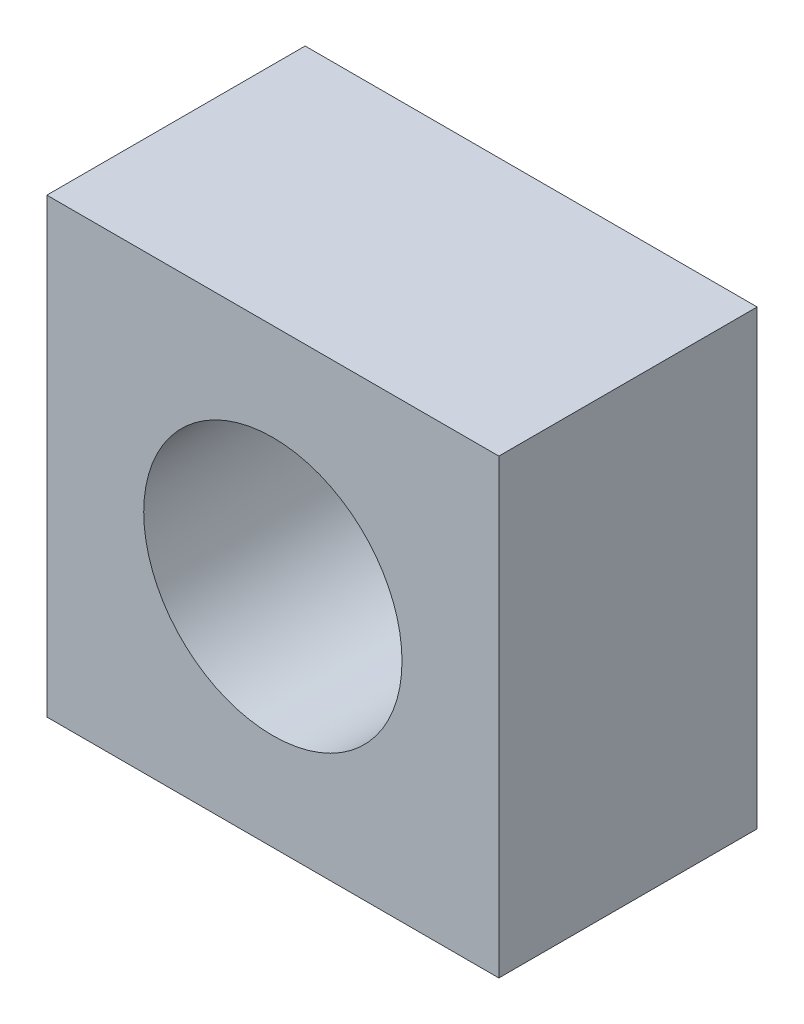
SolidWorks part; units mm, degrees
material "Tin Bearing Bronze"
ref_plane "Front Plane" through (0, 0, 0) normal (0, 0, 1) x (1, 0, 0)
ref_plane "Top Plane" through (0, 0, 0) normal (0, 1, 0) x (1, 0, 0)
ref_plane "Right Plane" through (0, 0, 0) normal (1, 0, 0) x (0, 0, -1)
sketch "Sketch1" plane through (0, 0, 0) normal (0, 0, 1) x (1, 0, 0)
  line L1 (-11.1125, -11.1125) -> (11.1125, -11.1125)
  line L2 (-11.1125, -11.1125) -> (-11.1125, 11.1125)
  line L3 (-11.1125, 11.1125) -> (11.1125, 11.1125)
  line L4 (11.1125, -11.1125) -> (11.1125, 11.1125)
  line L5 (-11.1125, -11.1125) -> (11.1125, 11.1125) construction
  line L6 (-11.1125, 11.1125) -> (11.1125, -11.1125) construction
  circle A0 centre (0, 0) radius 6.35
  point P0 (0, 0)
  dimension "D3" = 12.7
  dimension "D1" = 22.225
  dimension "D2" = 22.225
extrude "Boss-Extrude1" add sketch "Sketch1" along normal blind 12.7
